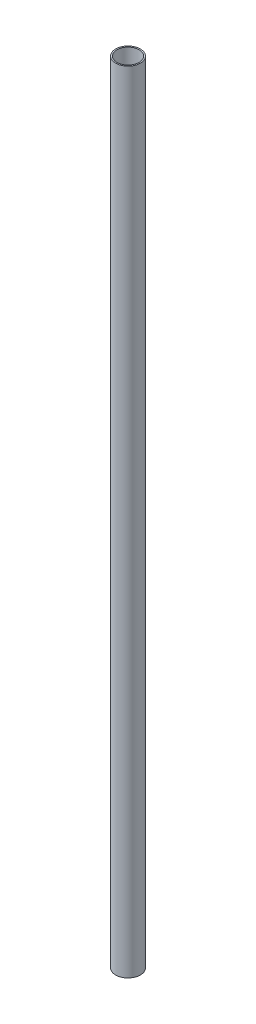
SolidWorks part; units mm, degrees
ref_plane "Front Plane" through (0, 0, 0) normal (0, 0, 1) x (1, 0, 0)
ref_plane "Top Plane" through (0, 0, 0) normal (0, 1, 0) x (1, 0, 0)
ref_plane "Right Plane" through (0, 0, 0) normal (1, 0, 0) x (0, 0, -1)
sketch "Sketch1" plane through (0, 0, 0) normal (0, 1, 0) x (1, 0, 0)
  circle A0 centre (0, 0) radius 4.7625
  circle A1 centre (0, 0) radius 4.2545
  dimension "D1" = 9.525
  dimension "D2" = 0.508
extrude "Boss-Extrude1" add sketch "Sketch1" along normal blind 304.8
